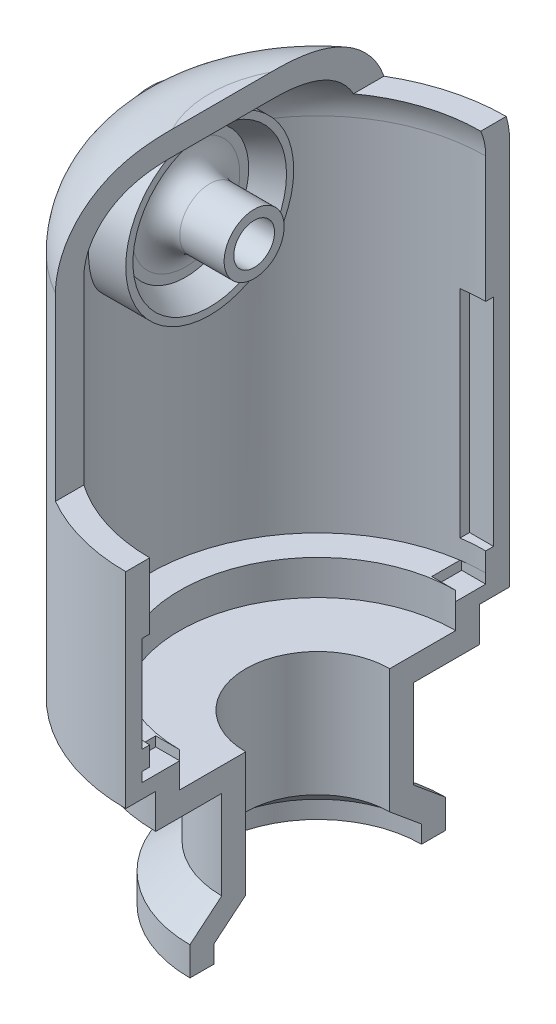
SolidWorks part; units mm, degrees
ref_plane "정면" through (0, 0, 0) normal (0, 0, 1) x (1, 0, 0)
ref_plane "윗면" through (0, 0, 0) normal (0, 1, 0) x (1, 0, 0)
ref_plane "우측면" through (0, 0, 0) normal (1, 0, 0) x (0, 0, -1)
sketch "스케치1" plane through (0, 0, 0) normal (0, 1, 0) x (1, 0, 0)
  circle A0 centre (0, 0) radius 16
  dimension "D1" = 32
extrude "보스-돌출1" add sketch "스케치1" along normal blind 54
sketch "스케치2" plane through (0, 0, 0) normal (0, 0, 1) x (1, 0, 0)
  line L0 (0, 0) -> (0, 55.3244) construction
  line L1 (19.2448, 14.9) -> (13.5, 14.9)
  line L2 (13.5, 14.9) -> (13.5, 12)
  line L3 (13.5, 12) -> (8, 12)
  line L4 (8, 12) -> (8, 4.6)
  line L5 (8, 4.6) -> (10.65, 2.4)
  line L6 (10.65, 2.4) -> (10.65, 0)
  line L7 (-16, 0) -> (16, 0) construction
  line L8 (10.65, 0) -> (19.2448, 0)
  line L9 (19.2448, 0) -> (19.2448, 14.9)
  line L10 (16, 0) -> (16, 54) construction
  dimension "D1" = 14.9
  dimension "D2" = 12
  dimension "D3" = 13.5
  dimension "D4" = 8
  dimension "D5" = 7.4
  dimension "D6" = 2.4
  dimension "D7" = 10.65
revolve "컷-회전1" cut sketch "스케치2" angle 360 about L0
fillet "필렛1" radius 7 1 edges at (0, 54, 16)
shell "쉘1" thickness 2
sketch "스케치3" plane through (0, 0, 0) normal (0, 0, 1) x (1, 0, 0)
  line L0 (0, 0) -> (0, 55.5876)
  line L1 (-10.65, 0) -> (10.65, 0) construction
  line L2 (0, 55.5876) -> (17.9947, 55.5876)
  line L3 (17.9947, 55.5876) -> (17.9947, 0)
  line L4 (17.9947, 0) -> (0, 0)
extrude "컷-돌출1" cut sketch "스케치3" against normal through all both and the other way through all
sketch "스케치4" plane through (0, 54, 0) normal (0, 1, 0) x (1, 0, 0)
  line L0 (-8, 0) -> (-8, -16.9798)
  line L1 (-8, -16.9798) -> (0, -16.9798)
  line L2 (0, -16.9798) -> (0, 0)
  line L3 (0, 0) -> (-8, 0)
  line L4 (0, 9) -> (0, -9) construction
  point P2 (0, 0)
  dimension "D1" = 8
extrude "컷-돌출3" cut sketch "스케치4" against normal blind 22
sketch "스케치5" plane through (0, 54, 0) normal (0, 1, 0) x (1, 0, 0)
  line L0 (-8, 16.3949) -> (-8, 0)
  line L1 (-8, 0) -> (-8, -4.1231) construction
  line L2 (-8, 0) -> (0, 0)
  line L3 (0, 0) -> (0, 16.3949)
  line L4 (0, 16.3949) -> (-8, 16.3949)
  point P7 (0, 0)
  point P8 (0, 0)
extrude "컷-돌출4" cut sketch "스케치5" against normal blind 5
ref_plane "평면1" through (-9, 0, 0) normal (1, 0, 0) x (0, 0, -1)
sketch "스케치6" plane through (-9, 0, 0) normal (1, 0, 0) x (0, 0, -1)
  line L0 (0, 0) -> (0, 59.8625) construction
  circle A0 centre (0, 45) radius 7
  dimension "D1" = 14
  dimension "D2" = 45
extrude "보스-돌출2" add sketch "스케치6" against normal up to surface (3.1244 mm away)
sketch "스케치7" plane through (-9, 0, 0) normal (1, 0, 0) x (0, 0, -1)
  circle A0 centre (0, 45) radius 2.5
  dimension "D1" = 5
sketch "스케치8" plane through (-9, 0, 0) normal (1, 0, 0) x (0, 0, -1)
  circle A0 centre (0, 45) radius 6.4
  dimension "D1" = 12.8
extrude "컷-돌출6" cut sketch "스케치8" against normal blind 2 draft 30
sketch "스케치10" plane through (0, 0, 0) normal (1, 0, 0) x (0, 0, -1)
  line L0 (-13.85, 18.5) -> (-14.65, 18.5)
  line L1 (-11.5, 14) -> (-11.5, 16.9) construction
  line L2 (-14.65, 18.5) -> (-14.65, 26.5)
  line L3 (-14.65, 26.5) -> (-13.85, 26.5)
  line L4 (-13.85, 26.5) -> (-13.85, 18.5)
  line L5 (-14.65, 16.9) -> (-14.65, 16.1)
  line L6 (-14.65, 16.1) -> (-11.5, 16.1)
  line L7 (-11.5, 16.1) -> (-11.5, 16.9)
  line L8 (11.5, 16.9) -> (11.5, 14) construction
  line L9 (-11.5, 16.9) -> (-14.65, 16.9)
  line L10 (11.5, 16.9) -> (11.5, 16.1)
  line L11 (14, 16.9) -> (11.5, 16.9) construction
  line L12 (11.5, 16.1) -> (14, 16.1)
  line L13 (14, 16.1) -> (14, 16.9)
  line L14 (14, 16.9) -> (11.5, 16.9)
  line L15 (13.85, 18.5) -> (14.65, 18.5)
  line L17 (14.65, 18.5) -> (14.65, 36.5)
  line L18 (14.65, 36.5) -> (13.85, 36.5)
  line L19 (13.85, 36.5) -> (13.85, 18.5)
  line L20 (14, 16.9) -> (-14, 16.9) construction
  line L21 (0, 0) -> (0, 44.5321) construction
  point P2 (0, 0)
  point P3 (0, 0)
  point P12 (0, 0)
  point P13 (-12.05, 15.7397)
  point P19 (-11.5, 16.1)
  point P29 (11.5, 16.1)
  point P32 (14, 16.9)
  dimension "D1" = 0.8
  dimension "D2" = 1.6
  dimension "D3" = 8
  dimension "D4" = 18
  dimension "D5" = 27.7
extrude "컷-돌출7" cut sketch "스케치10" against normal blind 2
extrude "보스-돌출3" add sketch "스케치7" along normal blind 3.7 and the other way up to surface (2 mm away) other way up to face at (-11, 45, -5.2453)
hole_wizard "M3 여유 구멍1" positions "3D스케치1" profile "스케치11" hole size "M3" standard "Ansi Metric" end condition through all
sketch3d "3D스케치1"
  line L0 (-11, 45, 0) -> (-5.3, 45, 0) construction
  point P0 (-5.3, 45, 0)
sketch "스케치11" plane through (-5.3, 45, 0) normal (0, 1, 0) x (0, 0, -1)
  line L0 (0, 0) -> (0, 10.7)
  line L1 (0, 10.7) -> (1.7, 10.7)
  line L2 (1.7, 10.7) -> (1.7, 0)
  line L5 (1.7, 0) -> (0, 0)
  line L11 (0, -6.35) -> (0, 107.95) construction
  dimension "관통 구멍 지름" = 3.4
  dimension "관통 구멍 깊이" = 10.7
fillet "필렛3" radius 2 1 edges at (-11, 45, -2.5)
